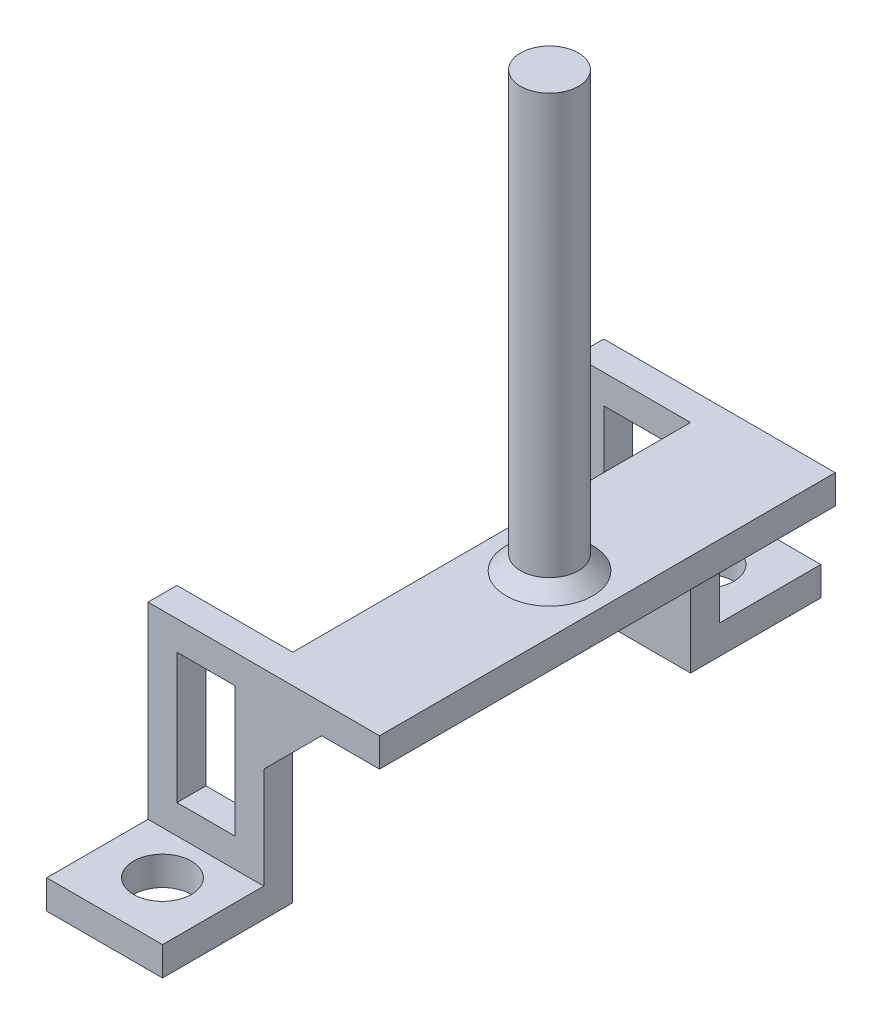
SolidWorks part; units mm, degrees
ref_plane "Front Plane" through (0, 0, 0) normal (0, 0, 1) x (1, 0, 0)
ref_plane "Top Plane" through (0, 0, 0) normal (0, 1, 0) x (1, 0, 0)
ref_plane "Right Plane" through (0, 0, 0) normal (1, 0, 0) x (0, 0, -1)
sketch "Sketch1" plane through (0, 0, 0) normal (0, 1, 0) x (1, 0, 0)
  line L0 (0, 0) -> (0, 37.5) construction
  line L1 (-4, 4) -> (4, 4)
  line L2 (-4, 4) -> (-4, -4)
  line L3 (-4, -4) -> (4, -4)
  line L4 (4, 4) -> (4, -4)
  line L5 (-4, 4) -> (4, -4) construction
  line L6 (-4, -4) -> (4, 4) construction
  line L8 (-4, 41.5) -> (4, 41.5)
  line L9 (-4, 41.5) -> (-4, 33.5)
  line L10 (-4, 33.5) -> (4, 33.5)
  line L11 (4, 41.5) -> (4, 33.5)
  line L12 (-4, 41.5) -> (4, 33.5) construction
  line L13 (-4, 33.5) -> (4, 41.5) construction
  circle A0 centre (0, 37.5) radius 2
  circle A1 centre (0, 0) radius 2
  point P0 (0, 0)
  dimension "D4" = 4
  dimension "D1" = 37.5
  dimension "D2" = 8
  dimension "D3" = 8
extrude "Boss-Extrude1" add sketch "Sketch1" along normal blind 2
sketch "Sketch2" plane through (0, 0, 0) normal (0, -1, 0) x (1, 0, 0)
  line L0 (-4, -41.5) -> (-4, -33.5) construction
  line L1 (-4, -34.5) -> (4, -34.5)
  line L2 (-4, -34.5) -> (-4, -32.5)
  line L3 (-4, -32.5) -> (4, -32.5)
  line L4 (4, -34.5) -> (4, -32.5)
  line L5 (-4, -33.5) -> (4, -33.5) construction
  line L6 (0, -37.5) -> (0, 0) construction
  line L7 (0, -18.75) -> (13.1261, -18.75) construction
  line L8 (-4, -5) -> (4, -5)
  line L9 (4, -3) -> (4, -5)
  line L10 (-4, -3) -> (4, -3)
  line L11 (-4, -3) -> (-4, -5)
  dimension "D1" = 8
  dimension "D2" = 2
  dimension "D3" = 1
extrude "Boss-Extrude2" add sketch "Sketch2" against normal blind 15
sketch "Sketch3" plane through (0, 0, -34.5) normal (0, 0, 1) x (1, 0, 0)
  line L6 (4, 15) -> (12, 15)
  line L7 (4, 15) -> (4, 13)
  line L8 (4, 13) -> (12, 13)
  line L9 (12, 15) -> (12, 13)
  dimension "D1" = 2
  dimension "D2" = 8
extrude "Boss-Extrude3" add sketch "Sketch3" along normal up to surface (31.5 mm away) up to face at (0, 8.5, -3)
chamfer "Chamfer1" distance 4 angle 45 2 edges at (4, 13, -33.5) (4, 13, -4)
sketch "Sketch4" plane through (0, 0, -3) normal (0, 0, 1) x (1, 0, 0)
  line L0 (0, 2) -> (0, 15) construction
  line L1 (-4, 2) -> (4, 2) construction
  line L2 (12, 15) -> (-4, 15) construction
  line L3 (-4, 15) -> (-4, 2) construction
  line L4 (-2, 4) -> (2, 4)
  line L5 (-2, 4) -> (-2, 13)
  line L6 (-2, 13) -> (2, 13)
  line L7 (2, 4) -> (2, 13)
  line L8 (-2, 4) -> (2, 13) construction
  line L9 (-2, 13) -> (2, 4) construction
  point P7 (0, 8.5)
  dimension "D1" = 2
  dimension "D2" = 2
extrude "Cut-Extrude1" cut sketch "Sketch4" against normal through all
sketch "Sketch5" plane through (0, 15, 0) normal (0, 1, 0) x (1, 0, 0)
  line L0 (4, 18.75) -> (12, 18.75) construction
  line L1 (4, 5) -> (4, 32.5) construction
  line L2 (12, 3) -> (12, 34.5) construction
  circle A0 centre (8, 18.75) radius 2
  dimension "D1" = 4
extrude "Boss-Extrude4" add sketch "Sketch5" along normal blind 30
chamfer "Chamfer2" distance 1 angle 45 1 edges at (8, 15, -20.75)
